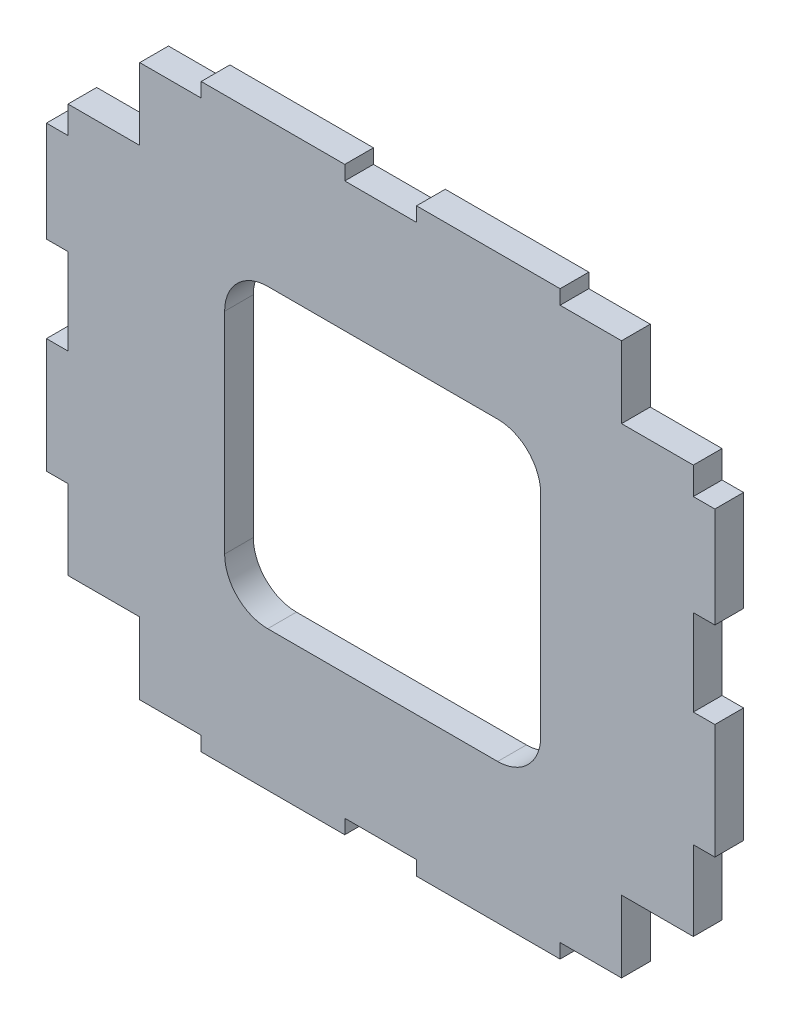
SolidWorks part; units mm, degrees
ref_plane "前视基准面" through (0, 0, 0) normal (0, 0, 1) x (1, 0, 0)
ref_plane "上视基准面" through (0, 0, 0) normal (0, 1, 0) x (1, 0, 0)
ref_plane "右视基准面" through (0, 0, 0) normal (1, 0, 0) x (0, 0, -1)
sketch "Model" plane through (0, 0, 0) normal (0, 0, 1) x (1, 0, 0)
  line L0 (56.9927, 38.8861) -> (40.9727, 38.8861)
  line L1 (40.9727, 18.2361) -> (56.9927, 18.2361)
  line L2 (59.9927, 35.8861) -> (59.9927, 21.2361)
  line L3 (37.9727, 35.8861) -> (37.9727, 21.2361)
  line L4 (32.061, 47.9303) -> (36.341, 47.9303)
  line L5 (36.341, 47.9303) -> (36.341, 48.9307)
  line L6 (36.341, 48.9307) -> (46.341, 48.9307)
  line L7 (46.341, 48.9307) -> (46.341, 47.9303)
  line L8 (46.341, 47.9303) -> (51.341, 47.9303)
  line L9 (51.341, 47.9303) -> (51.341, 48.9307)
  line L10 (51.341, 48.9307) -> (61.341, 48.9307)
  line L11 (61.341, 48.9307) -> (61.341, 47.9303)
  line L12 (61.341, 47.9303) -> (65.621, 47.9303)
  line L13 (32.061, 9.4882) -> (36.341, 9.4882)
  line L14 (36.341, 9.4882) -> (36.341, 8.4879)
  line L15 (36.341, 8.4879) -> (46.341, 8.4879)
  line L16 (46.341, 8.4879) -> (46.341, 9.4882)
  line L17 (46.341, 9.4882) -> (51.341, 9.4882)
  line L18 (51.341, 9.4882) -> (51.341, 8.4879)
  line L19 (51.341, 8.4879) -> (61.341, 8.4879)
  line L20 (61.341, 8.4879) -> (61.341, 9.4882)
  line L21 (61.341, 9.4882) -> (65.621, 9.4882)
  line L22 (27.061, 42.9303) -> (32.061, 42.9303)
  line L23 (32.061, 42.9303) -> (32.061, 47.9303)
  line L24 (27.061, 14.4882) -> (32.061, 14.4882)
  line L25 (32.061, 14.4882) -> (32.061, 9.4882)
  line L26 (27.061, 42.9303) -> (27.061, 41.0303)
  line L27 (27.061, 41.0303) -> (25.561, 41.0303)
  line L28 (25.561, 41.0303) -> (25.561, 34.0303)
  line L29 (25.561, 34.0303) -> (27.061, 34.0303)
  line L30 (27.061, 34.0303) -> (27.061, 28.0303)
  line L31 (27.061, 28.0303) -> (25.561, 28.0303)
  line L32 (25.561, 28.0303) -> (25.561, 20.0303)
  line L33 (25.561, 20.0303) -> (27.061, 20.0303)
  line L34 (27.061, 20.0303) -> (27.061, 14.4882)
  line L35 (70.621, 42.9303) -> (65.621, 42.9303)
  line L36 (65.621, 42.9303) -> (65.621, 47.9303)
  line L37 (70.621, 14.4882) -> (65.621, 14.4882)
  line L38 (65.621, 14.4882) -> (65.621, 9.4882)
  line L39 (70.621, 42.9303) -> (70.621, 41.0303)
  line L40 (70.621, 41.0303) -> (72.121, 41.0303)
  line L41 (72.121, 41.0303) -> (72.121, 34.0303)
  line L42 (72.121, 34.0303) -> (70.621, 34.0303)
  line L43 (70.621, 34.0303) -> (70.621, 28.0303)
  line L44 (70.621, 28.0303) -> (72.121, 28.0303)
  line L45 (72.121, 28.0303) -> (72.121, 20.0303)
  line L46 (72.121, 20.0303) -> (70.621, 20.0303)
  line L47 (70.621, 20.0303) -> (70.621, 14.4882)
  arc A0 (40.9727, 38.8861) -> (37.9727, 35.8861) centre (40.9727, 35.8861) ccw
  arc A1 (56.9927, 18.2361) -> (59.9927, 21.2361) centre (56.9927, 21.2361) ccw
  arc A2 (59.9927, 35.8861) -> (56.9927, 38.8861) centre (56.9927, 35.8861) ccw
  arc A3 (37.9727, 21.2361) -> (40.9727, 18.2361) centre (40.9727, 21.2361) ccw
extrude "凸台-拉伸1" add sketch "Model" along normal blind 2
